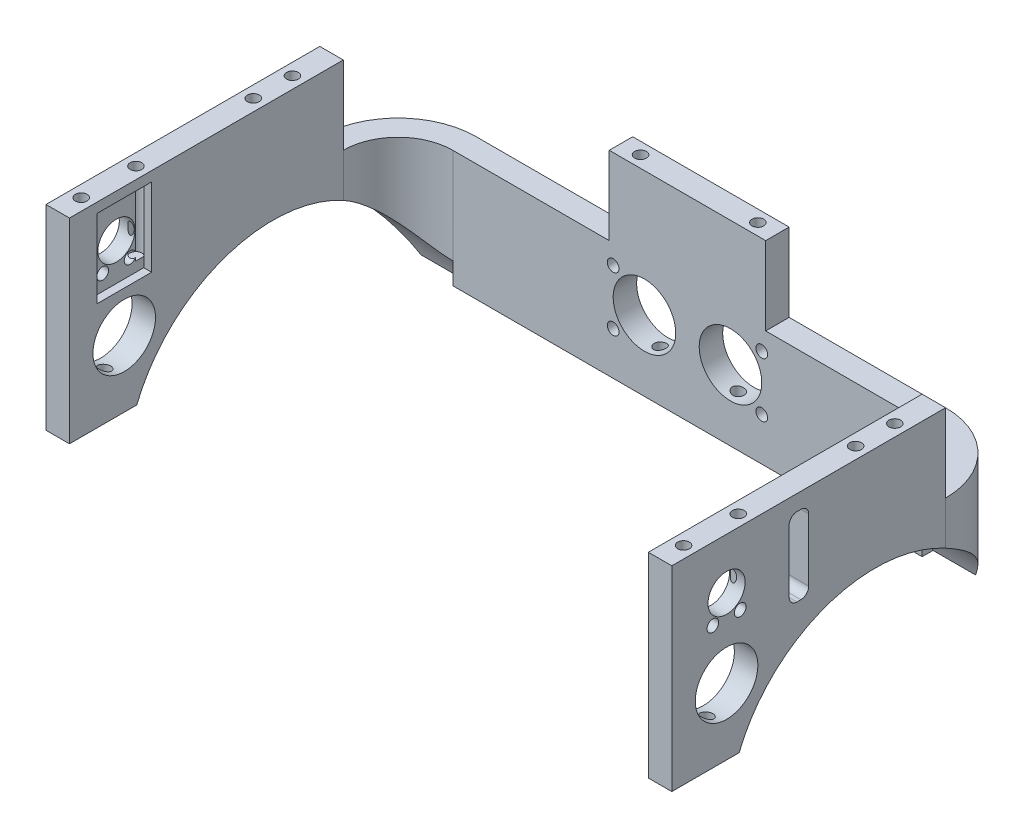
SolidWorks part; units mm, degrees
ref_plane "Alzado" through (0, 0, 0) normal (0, 0, 1) x (1, 0, 0)
ref_plane "Planta" through (0, 0, 0) normal (0, 1, 0) x (1, 0, 0)
ref_plane "Vista lateral" through (0, 0, 0) normal (1, 0, 0) x (0, 0, -1)
sketch "Croquis1" plane through (0, 0, 0) normal (0, 1, 0) x (1, 0, 0)
  line L0 (-20, -6) -> (-140, -6)
  line L1 (-20, 0) -> (-140, 0)
  line L2 (0, -20) -> (0, -90)
  line L3 (0, -90) -> (-6, -90)
  line L4 (-160, -20) -> (-160, -90)
  line L5 (-154, -20) -> (-154, -84)
  line L7 (-6, -20) -> (-6, -84)
  line L8 (-154, -84) -> (-154, -90)
  line L9 (-6, -84) -> (-6, -90)
  line L10 (-154, -90) -> (-160, -90)
  line L11 (-6, -84) -> (-154, -84) construction
  line L12 (0, -90) -> (-160, -90) construction
  arc A0 (-140, 0) -> (-160, -20) centre (-140, -20) ccw
  arc A1 (-20, 0) -> (0, -20) centre (-20, -20) cw
  arc A2 (-140, -6) -> (-154, -20) centre (-140, -20) ccw
  arc A3 (-20, -6) -> (-6, -20) centre (-20, -20) cw
  point P7 (-160, 0)
  point P10 (0, 0)
  dimension "D3" = 20
  dimension "D4" = 20
  dimension "D1" = 160
  dimension "D2" = 90
  dimension "D5" = 6
extrude "Saliente-Extruir1" add sketch "Croquis1" along normal blind 50
sketch "Croquis3" plane through (0, 50, 0) normal (0, 1, 0) x (1, 0, 0)
  line L0 (-20, 0) -> (-140, 0) construction
  line L1 (-160, -20) -> (-100, -20)
  line L2 (-160, -20) -> (-160, 0)
  line L3 (-160, 0) -> (-100, 0)
  line L4 (-100, -20) -> (-100, 0)
  line L5 (-80, 17.259) -> (-80, -96.2996) construction
  line L6 (0, -20) -> (-60, -20)
  line L7 (0, -20) -> (0, 0)
  line L8 (0, 0) -> (-60, 0)
  line L9 (-60, -20) -> (-60, 0)
  line L10 (-6, -20) -> (-6, -90) construction
  line L11 (-154, -90) -> (-154, -20) construction
  dimension "D1" = 40
extrude "Cortar-Extruir1" cut sketch "Croquis3" against normal blind 20
sketch "Croquis4" plane through (0, 0, 0) normal (0, 0, -1) x (-1, 0, 0)
  line L0 (80, 58.2909) -> (80, -24.7014) construction
  line L1 (160, 30) -> (160, 0) construction
  line L2 (0, 30) -> (0, 0) construction
  line L3 (20, 30) -> (60, 30) construction
  line L4 (56.6513, 18) -> (103.771, 18) construction
  circle A0 centre (69, 18) radius 8
  circle A1 centre (91, 18) radius 8
  circle A2 centre (61, 25) radius 1.5
  circle A3 centre (99, 25) radius 1.5
  circle A4 centre (99, 11) radius 1.5
  circle A5 centre (61, 11) radius 1.5
  dimension "D1" = 16
  dimension "D4" = 3
  dimension "D2" = 22
  dimension "D3" = 12
  dimension "D5" = 14
  dimension "D6" = 38
extrude "Cortar-Extruir2" cut sketch "Croquis4" against normal blind 10
sketch "Croquis5" plane through (0, 0, 0) normal (1, 0, 0) x (0, 0, -1)
  line L0 (-90, 50) -> (-90, 0) construction
  line L1 (-90, 0) -> (-20, 0) construction
  line L2 (-76, 53.3156) -> (-76, -1.46) construction
  circle A0 centre (-76, 17) radius 8
  circle A1 centre (-76, 37) radius 4.75
  circle A2 centre (-72.5, 31.5) radius 1.5
  circle A3 centre (-79.5, 31.5) radius 1.5
  dimension "D1" = 16
  dimension "D4" = 9.5
  dimension "D5" = 3
  dimension "D2" = 14
  dimension "D3" = 17
  dimension "D6" = 7
  dimension "D7" = 5.5
  dimension "D8" = 20
extrude "Cortar-Extruir3" cut sketch "Croquis5" against normal blind 172
sketch "Croquis6" plane through (-154, 0, 0) normal (1, 0, 0) x (0, 0, -1)
  line L0 (-76, 45.0758) -> (-76, 25.7834) construction
  line L1 (-83, 47.5) -> (-69, 47.5)
  line L2 (-83, 47.5) -> (-83, 27.5)
  line L3 (-83, 27.5) -> (-69, 27.5)
  line L4 (-69, 47.5) -> (-69, 27.5)
  circle A0 centre (-76, 37) radius 4.75
  circle A1 centre (-76, 37) radius 4.75 construction
  dimension "D1" = 20
  dimension "D2" = 14
  dimension "D3" = 9.5
extrude "Cortar-Extruir4" cut sketch "Croquis6" against normal blind 2
sketch "Croquis7" plane through (-6, 0, 0) normal (-1, 0, 0) x (0, 0, 1)
  line L0 (76, 49) -> (76, 25) construction
  line L1 (69, 47.5) -> (83, 47.5)
  line L2 (69, 47.5) -> (69, 27.5)
  line L3 (69, 27.5) -> (83, 27.5)
  line L4 (83, 47.5) -> (83, 27.5)
  circle A0 centre (76, 17) radius 8 construction
  circle A1 centre (76, 37) radius 4.75
  circle A2 centre (76, 37) radius 4.75 construction
  circle A3 centre (76, 37) radius 4.75 construction
  dimension "D1" = 14
  dimension "D2" = 20
  dimension "D3" = 9.5
extrude "Cortar-Extruir5" cut sketch "Croquis7" against normal blind 2
sketch "Croquis8" plane through (-160, 0, 0) normal (-1, 0, 0) x (0, 0, 1)
  line L0 (90, 50) -> (90, 0) construction
  line L1 (20, 0) -> (90, 0) construction
  circle A0 centre (38, -14) radius 37.5
  dimension "D1" = 52
  dimension "D3" = 75
  dimension "D2" = 14
extrude "Cortar-Extruir6" cut sketch "Croquis8" against normal blind 20
sketch "Croquis9" plane through (0, 0, 0) normal (1, 0, 0) x (0, 0, -1)
  line L0 (-90, 0) -> (-20, 0) construction
  line L2 (-90, 50) -> (-90, 0) construction
  circle A0 centre (-38, -14) radius 37.5
  dimension "D1" = 75
  dimension "D2" = 14
  dimension "D3" = 52
extrude "Cortar-Extruir7" cut sketch "Croquis9" against normal blind 20
sketch "Croquis10" plane through (0, 0, 0) normal (0, -1, 0) x (-1, 0, 0)
  line L0 (80, -108.4206) -> (80, 18.3585) construction
  line L1 (20, 0) -> (140, 0) construction
  line L2 (0, -20) -> (0, -72.7886) construction
  line L3 (160, -72.7886) -> (160, -20) construction
  line L4 (160, -72.7886) -> (160, -90) construction
  line L7 (160, -90) -> (154, -90) construction
  circle A0 centre (90, -3) radius 1.5
  circle A1 centre (110, -3) radius 1.5
  circle A2 centre (130, -3) radius 1.5
  circle A3 centre (70, -3) radius 1.5
  circle A4 centre (50, -3) radius 1.5
  circle A5 centre (30, -3) radius 1.5
  circle A6 centre (157, -86) radius 1.5
  circle A7 centre (157, -78) radius 1.5
  circle A8 centre (3, -86) radius 1.5
  circle A9 centre (3, -78) radius 1.5
  dimension "D1" = 20
  dimension "D4" = 3
  dimension "D6" = 3
  dimension "D2" = 60
  dimension "D3" = 100
  dimension "D5" = 3
  dimension "D7" = 4
  dimension "D8" = 8
extrude "Cortar-Extruir8" cut sketch "Croquis10" against normal blind 20
sketch "Croquis11" plane through (0, 50, 0) normal (0, 1, 0) x (1, 0, 0)
  line L0 (-80, 8.9465) -> (-80, -94.662) construction
  line L1 (-6, -90) -> (0, -90) construction
  line L2 (0, -90) -> (0, -20) construction
  line L3 (-160, -20) -> (-160, -90) construction
  line L5 (-100, -6) -> (-60, -6) construction
  circle A0 centre (-157, -84) radius 1.5
  circle A1 centre (-157, -70) radius 1.5
  circle A2 centre (-157, -40) radius 1.5
  circle A3 centre (-157, -30) radius 1.5
  circle A6 centre (-3, -30) radius 1.5
  circle A7 centre (-3, -40) radius 1.5
  circle A8 centre (-3, -70) radius 1.5
  circle A9 centre (-3, -84) radius 1.5
  circle A10 centre (-95, -3) radius 1.5
  circle A11 centre (-65, -3) radius 1.5
  dimension "D1" = 6
  dimension "D5" = 3
  dimension "D2" = 20
  dimension "D3" = 50
  dimension "D4" = 60
  dimension "D6" = 15
  dimension "D7" = 3
  dimension "D8" = 3
extrude "Cortar-Extruir9" cut sketch "Croquis11" against normal blind 20
sketch "Croquis12" plane through (0, 0, 0) normal (1, 0, 0) x (0, 0, -1)
  line L0 (-90, 50) -> (-90, 0) construction
  line L1 (-90, 50) -> (-20, 50) construction
  line L2 (-58, 46) -> (-57, 46)
  line L3 (-60, 44) -> (-60, 28)
  line L4 (-58, 26) -> (-57, 26)
  line L5 (-55, 44) -> (-55, 28)
  arc A0 (-57, 26) -> (-55, 28) centre (-57, 28) ccw
  arc A1 (-60, 28) -> (-58, 26) centre (-58, 28) ccw
  arc A2 (-58, 46) -> (-60, 44) centre (-58, 44) ccw
  arc A3 (-57, 46) -> (-55, 44) centre (-57, 44) cw
  point P12 (-60, 26)
  point P15 (-60, 46)
  point P18 (-55, 46)
  dimension "D5" = 2
  dimension "D1" = 5
  dimension "D2" = 20
  dimension "D3" = 30
  dimension "D4" = 4
extrude "Cortar-Extruir10" cut sketch "Croquis12" against normal blind 10
